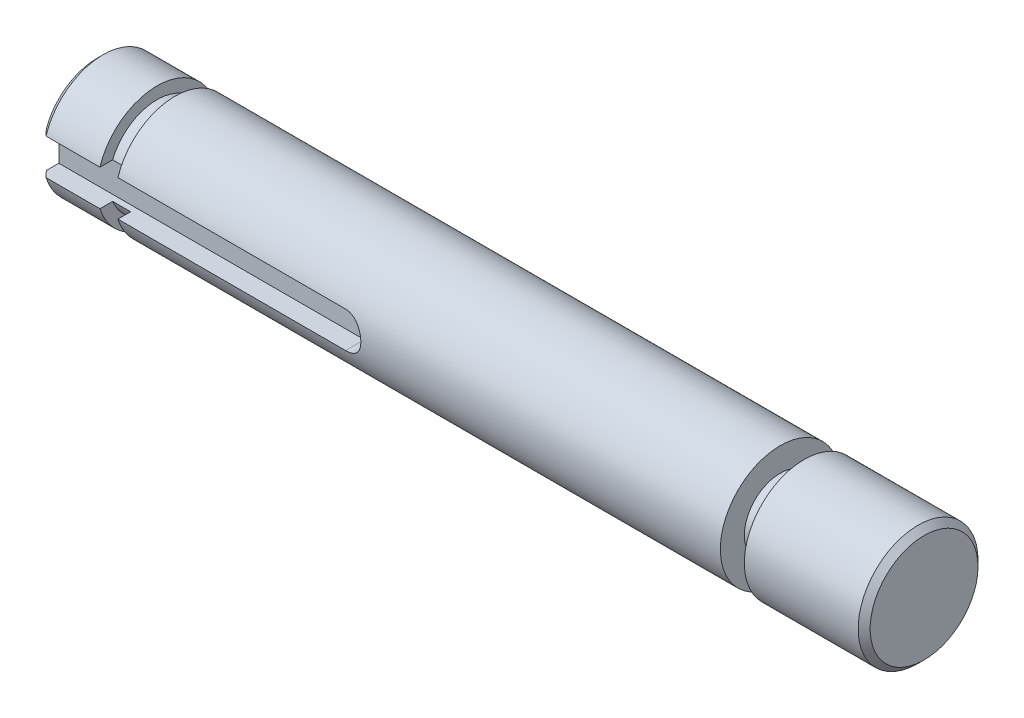
SolidWorks part; units mm, degrees
ref_plane "Front Plane" through (0, 0, 0) normal (0, 0, 1) x (1, 0, 0)
ref_plane "Top Plane" through (0, 0, 0) normal (0, 1, 0) x (1, 0, 0)
ref_plane "Right Plane" through (0, 0, 0) normal (1, 0, 0) x (0, 0, -1)
sketch "Sketch1" plane through (0, 0, 0) normal (1, 0, 0) x (0, 0, -1)
  circle A0 centre (0, 0) radius 5
  dimension "D1" = 10
extrude "Boss-Extrude1" add sketch "Sketch1" along normal mid plane 69
cosmetic thread "Cosmetic Thread2" parameters "D1"=9, "D2"=6.619
sketch "Sketch2" plane through (34.5, 0, 0) normal (1, 0, 0) x (0, 0, -1)
  circle A0 centre (0, 0) radius 3
  circle A1 centre (0, 0) radius 5
  circle A2 centre (0, 0) radius 5
  dimension "D2" = 6
  dimension "D1" = 0
extrude "Cut-Extrude1" cut sketch "Sketch2" against normal blind 2 from offset 10 offset against normal yes
sketch "Sketch3" plane through (-34.5, 0, 0) normal (-1, 0, 0) x (0, 0, 1)
  circle A0 centre (0, 0) radius 4
  circle A1 centre (0, 0) radius 5
  circle A2 centre (0, 0) radius 5
  dimension "D2" = 8
  dimension "D1" = 0
extrude "Cut-Extrude2" cut sketch "Sketch3" against normal blind 1.5 from offset 5 offset against normal yes
chamfer "Chamfer1" distance 0.5 angle 45 2 edges at (34.5, 0, -5) (-34.5, 0, -5)
sketch "Sketch4" plane through (0, 0, 0) normal (0, 0, 1) x (1, 0, 0)
  line L0 (-34.5, 0) -> (-9, 0) construction
  line L1 (-34.5, 4.5) -> (-34.5, -4.5) construction
  line L2 (-34.5, 1.5) -> (-9, 1.5)
  line L3 (-34.5, -1.5) -> (-9, -1.5)
  line L4 (-34.5, 1.5) -> (-34.5, -1.5)
  arc A1 (-9, -1.5) -> (-9, 1.5) centre (-9, 0) ccw
  point P5 (-23.6225, 0)
  dimension "D2" = 1.5
  dimension "D1" = 25.5
  dimension "D3" = 1.5
  dimension "D4" = 3
extrude "Cut-Extrude3" cut sketch "Sketch4" along normal through all from offset 3.2
